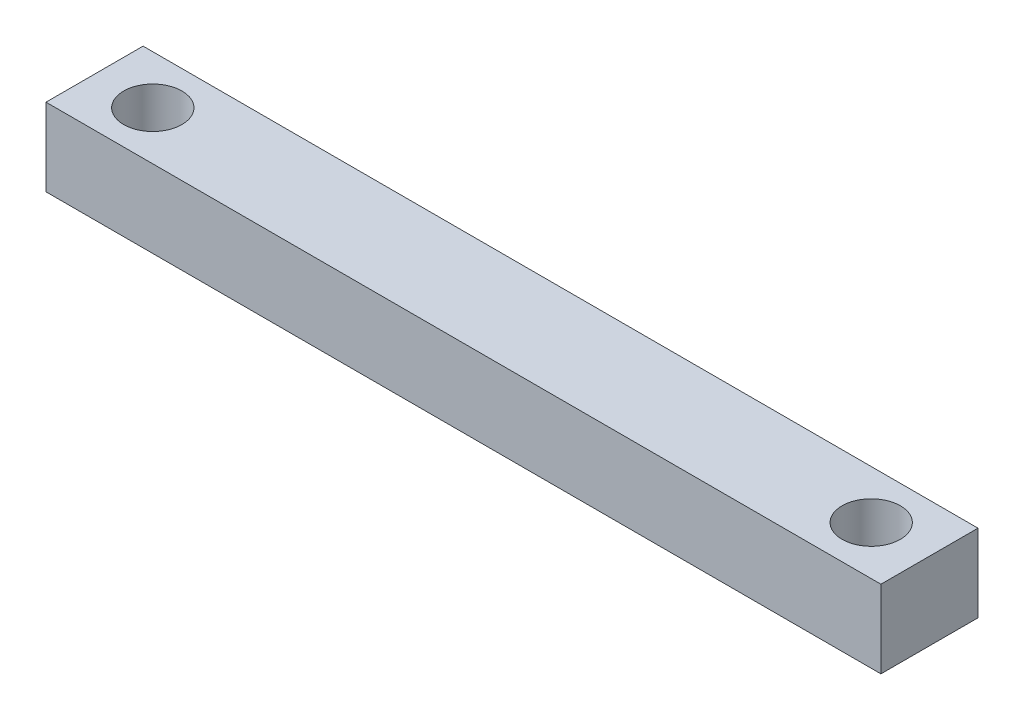
SolidWorks part; units mm, degrees
ref_plane "Спереди" through (0, 0, 0) normal (0, 0, 1) x (1, 0, 0)
ref_plane "Сверху" through (0, 0, 0) normal (0, 1, 0) x (1, 0, 0)
ref_plane "Справа" through (0, 0, 0) normal (1, 0, 0) x (0, 0, -1)
sketch "Эскиз1" plane through (0, 0, 0) normal (0, 1, 0) x (1, 0, 0)
  line L1 (-70.219, 8.163) -> (-27.219, 8.163)
  line L2 (-70.219, 8.163) -> (-70.219, 3.163)
  line L3 (-70.219, 3.163) -> (-27.219, 3.163)
  line L4 (-27.219, 8.163) -> (-27.219, 3.163)
  dimension "D1" = 5
  dimension "D2" = 43
extrude "Бобышка-Вытянуть1" add sketch "Эскиз1" along normal blind 4
sketch "Эскиз2" plane through (0, 4, 0) normal (0, 1, 0) x (-1, 0, 0)
  line L0 (70.219, -5.663) -> (27.219, -5.663) construction
  line L1 (70.219, -8.163) -> (70.219, -3.163) construction
  line L2 (27.219, -3.163) -> (27.219, -8.163) construction
  circle A0 centre (67.219, -5.663) radius 1.5
  circle A1 centre (30.219, -5.663) radius 1.5
  dimension "D1" = 3
  dimension "D2" = 3
  dimension "D4" = 3
  dimension "D3" = 3
extrude "Вырез-Вытянуть1" cut sketch "Эскиз2" against normal blind 4
